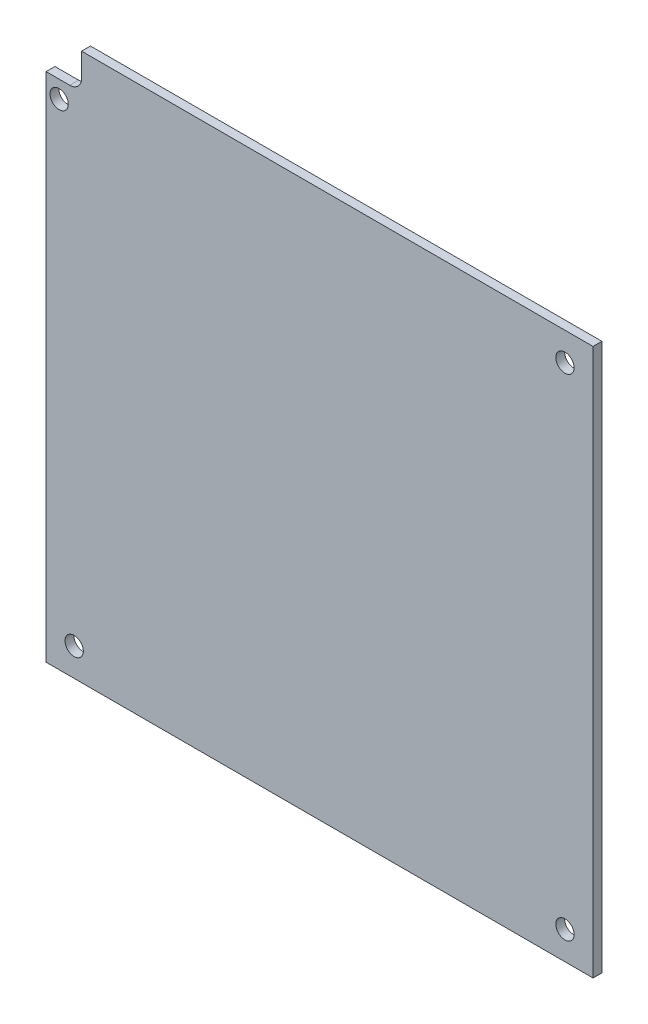
SolidWorks part; units mm, degrees
material "FR4"
ref_plane "Front Plane" through (0, 0, 0) normal (0, 0, 1) x (1, 0, 0)
ref_plane "Top Plane" through (0, 0, 0) normal (0, 1, 0) x (1, 0, 0)
ref_plane "Right Plane" through (0, 0, 0) normal (1, 0, 0) x (0, 0, -1)
sketch "Sketch1" plane through (0, 0, 0) normal (0, 0, 1) x (1, 0, 0)
  line L1 (46.25, -46.25) -> (-46.25, -46.25)
  line L2 (46.25, -46.25) -> (46.25, 46.25)
  line L3 (46.25, 46.25) -> (-46.25, 46.25)
  line L4 (-46.25, -46.25) -> (-46.25, 46.25)
  line L5 (46.25, -46.25) -> (-46.25, 46.25) construction
  line L6 (46.25, 46.25) -> (-46.25, -46.25) construction
  point P0 (0, 0)
  dimension "D1" = 92.5
  dimension "D2" = 92.5
extrude "Boss-Extrude1" add sketch "Sketch1" along normal blind 1.5
hole_wizard "Ø3.1 (3.1) Diameter Hole1" positions "Sketch3" profile "Sketch2" hole size "Ø3.1" standard "ANSI Metric" end condition through all
sketch "Sketch3" plane through (0, 0, 1.5) normal (0, 0, 1) x (1, 0, 0)
  point P0 (-44.05, 37.328)
  point P2 (41.5, 41.5)
  point P4 (41.5, -41.5)
  point P6 (-41.5, -41.5)
sketch "Sketch2" plane through (-44.05, 37.328, 1.5) normal (1, 0, 0) x (0, -1, 0)
  line L0 (0, 0) -> (0, 1.5)
  line L1 (0, 1.5) -> (1.55, 1.5)
  line L2 (1.55, 1.5) -> (1.55, 0)
  line L5 (1.55, 0) -> (0, 0)
  line L11 (0, -6.35) -> (0, 107.95) construction
  dimension "Thru Hole Dia." = 3.1
  dimension "Thru Hole Depth" = 1.5
sketch "Sketch6" plane through (0, 0, 0) normal (0, 0, -1) x (-1, 0, 0)
  line L0 (40.25, 46.25) -> (40.25, 42.25)
  line L1 (-46.25, 46.25) -> (46.25, 46.25) construction
  line L2 (42.25, 40.25) -> (46.25, 40.25)
  line L3 (46.25, 46.25) -> (46.25, -46.25) construction
  line L4 (40.25, 46.25) -> (46.25, 46.25)
  line L5 (46.25, 46.25) -> (46.25, 40.25)
  line L6 (46.25, 40.25) -> (46.3053, 40.2309)
  arc A0 (42.25, 40.25) -> (40.25, 42.25) centre (42.25, 42.25) cw
  point P9 (40.25, 40.25)
  line M17 (46.25, -46.25) -> (46.25, 46.25)
  line M18 (46.25, 46.25) -> (-46.25, 46.25)
  dimension "D3" = 2
  dimension "D1" = 6
  dimension "D2" = 0
  dimension "D4" = 6
extrude "Cut-Extrude1" cut sketch "Sketch6" against normal blind 10 contours A0 L2 L0 M17 M18
